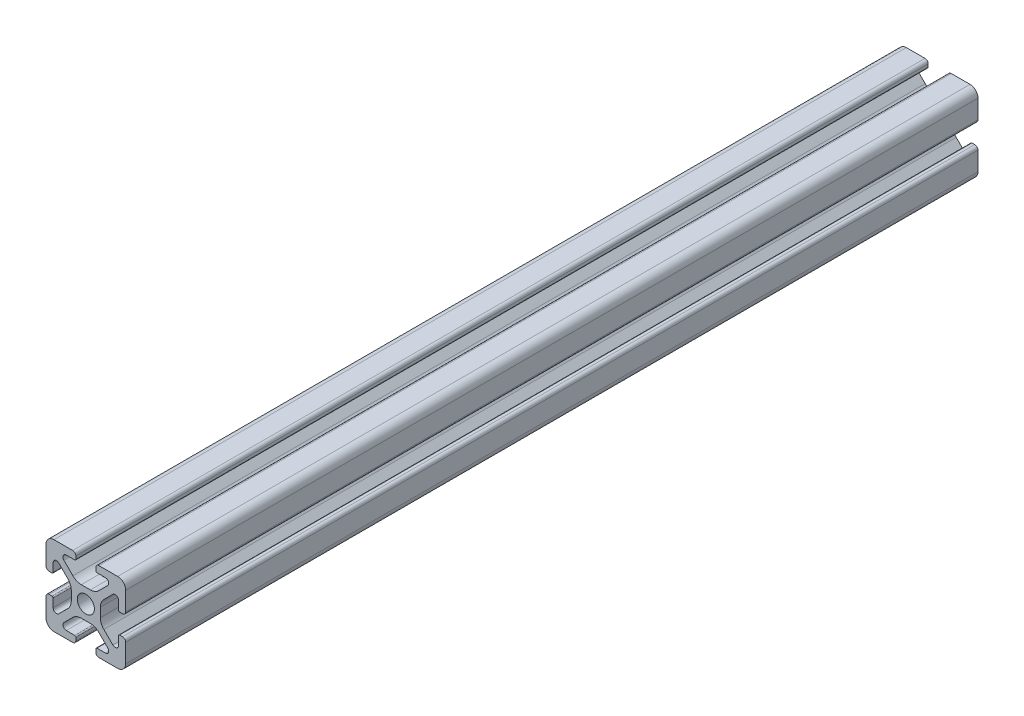
SolidWorks part; units mm, degrees
material "Alliage 1060"
ref_plane "Plan de face" through (0, 0, 0) normal (0, 0, 1) x (1, 0, 0)
ref_plane "Plan de dessus" through (0, 0, 0) normal (0, 1, 0) x (1, 0, 0)
ref_plane "Plan de droite" through (0, 0, 0) normal (1, 0, 0) x (0, 0, -1)
ref_plane "Plan1" through (0, 0, 0) normal (0, 0, -1) x (-1, 0, 0)
sketch "Esquisse1" plane through (0, 0, 0) normal (0, 0, -1) x (-1, 0, 0)
  line L0 (-18, 0) -> (-13.3, 0)
  line L1 (-12.8, 1.8) -> (-14.9184, 1.8)
  line L2 (-15.5064, 3.2196) -> (-13.2547, 5.4713)
  line L3 (-11.1334, 6.35) -> (-8.8666, 6.35)
  line L4 (-6.7453, 5.4713) -> (-4.4936, 3.2196)
  line L5 (-5.0816, 1.8) -> (-7.2, 1.8)
  line L6 (-6.7, 0) -> (-2, 0)
  line L7 (0, 2) -> (0, 6.7)
  line L8 (-1.8, 7.2) -> (-1.8, 5.0816)
  line L9 (-3.2196, 4.4936) -> (-5.4713, 6.7453)
  line L10 (-6.35, 8.8666) -> (-6.35, 11.1334)
  line L11 (-5.4713, 13.2547) -> (-3.2196, 15.5064)
  line L12 (-1.8, 14.9184) -> (-1.8, 12.8)
  line L13 (0, 13.3) -> (0, 18)
  line L14 (-2, 20) -> (-6.7, 20)
  line L15 (-7.2, 18.2) -> (-5.0816, 18.2)
  line L16 (-4.4936, 16.7804) -> (-6.7453, 14.5287)
  line L17 (-8.8666, 13.65) -> (-11.1334, 13.65)
  line L18 (-13.2547, 14.5287) -> (-15.5064, 16.7804)
  line L19 (-14.9184, 18.2) -> (-12.8, 18.2)
  line L20 (-13.3, 20) -> (-18, 20)
  line L21 (-20, 18) -> (-20, 13.3)
  line L22 (-16.7804, 15.5064) -> (-14.5287, 13.2547)
  line L23 (-13.65, 11.1334) -> (-13.65, 8.8666)
  line L24 (-14.5287, 6.7453) -> (-16.7804, 4.4936)
  line L25 (-18.2, 5.0816) -> (-18.2, 7.2)
  line L26 (-20, 6.7) -> (-20, 2)
  arc A0 (-20, 2) -> (-18, 0) centre (-18, 2) ccw
  arc A1 (-13.3, 0) -> (-12.5, 0.8) centre (-13.3, 0.8) ccw
  arc A2 (-12.5, 1.5) -> (-12.8, 1.8) centre (-12.8, 1.5) ccw
  arc A3 (-14.9184, 1.8) -> (-15.5064, 3.2196) centre (-14.9184, 2.6316) cw
  arc A4 (-13.2547, 5.4713) -> (-11.1334, 6.35) centre (-11.1334, 3.35) cw
  arc A5 (-8.8666, 6.35) -> (-6.7453, 5.4713) centre (-8.8666, 3.35) cw
  arc A6 (-4.4936, 3.2196) -> (-5.0816, 1.8) centre (-5.0816, 2.6316) cw
  arc A7 (-7.2, 1.8) -> (-7.5, 1.5) centre (-7.2, 1.5) ccw
  arc A8 (-7.5, 0.8) -> (-6.7, 0) centre (-6.7, 0.8) ccw
  arc A9 (-2, 0) -> (0, 2) centre (-2, 2) ccw
  arc A10 (0, 6.7) -> (-0.8, 7.5) centre (-0.8, 6.7) ccw
  arc A11 (-1.5, 7.5) -> (-1.8, 7.2) centre (-1.5, 7.2) ccw
  arc A12 (-1.8, 5.0816) -> (-3.2196, 4.4936) centre (-2.6316, 5.0816) cw
  arc A13 (-5.4713, 6.7453) -> (-6.35, 8.8666) centre (-3.35, 8.8666) cw
  arc A14 (-6.35, 11.1334) -> (-5.4713, 13.2547) centre (-3.35, 11.1334) cw
  arc A15 (-3.2196, 15.5064) -> (-1.8, 14.9184) centre (-2.6316, 14.9184) cw
  arc A16 (-1.8, 12.8) -> (-1.5, 12.5) centre (-1.5, 12.8) ccw
  arc A17 (-0.8, 12.5) -> (0, 13.3) centre (-0.8, 13.3) ccw
  arc A18 (0, 18) -> (-2, 20) centre (-2, 18) ccw
  arc A19 (-6.7, 20) -> (-7.5, 19.2) centre (-6.7, 19.2) ccw
  arc A20 (-7.5, 18.5) -> (-7.2, 18.2) centre (-7.2, 18.5) ccw
  arc A21 (-5.0816, 18.2) -> (-4.4936, 16.7804) centre (-5.0816, 17.3684) cw
  arc A22 (-6.7453, 14.5287) -> (-8.8666, 13.65) centre (-8.8666, 16.65) cw
  arc A23 (-11.1334, 13.65) -> (-13.2547, 14.5287) centre (-11.1334, 16.65) cw
  arc A24 (-15.5064, 16.7804) -> (-14.9184, 18.2) centre (-14.9184, 17.3684) cw
  arc A25 (-12.8, 18.2) -> (-12.5, 18.5) centre (-12.8, 18.5) ccw
  arc A26 (-12.5, 19.2) -> (-13.3, 20) centre (-13.3, 19.2) ccw
  arc A27 (-18, 20) -> (-20, 18) centre (-18, 18) ccw
  arc A28 (-20, 13.3) -> (-19.2, 12.5) centre (-19.2, 13.3) ccw
  arc A29 (-18.5, 12.5) -> (-18.2, 12.8) centre (-18.5, 12.8) ccw
  arc A30 (-18.2, 14.9184) -> (-16.7804, 15.5064) centre (-17.3684, 14.9184) cw
  arc A31 (-14.5287, 13.2547) -> (-13.65, 11.1334) centre (-16.65, 11.1334) cw
  arc A32 (-13.65, 8.8666) -> (-14.5287, 6.7453) centre (-16.65, 8.8666) cw
  arc A33 (-16.7804, 4.4936) -> (-18.2, 5.0816) centre (-17.3684, 5.0816) cw
  arc A34 (-18.2, 7.2) -> (-18.5, 7.5) centre (-18.5, 7.2) ccw
  arc A35 (-19.2, 7.5) -> (-20, 6.7) centre (-19.2, 6.7) ccw
  circle A36 centre (-10, 10) radius 2.15
  spline S0 degree 1 poles (-12.5, 1.5) (-12.5, 0.8) knots 0 0 0.7 0.7
  spline S1 degree 1 poles (-7.5, 0.8) (-7.5, 1.5) knots 0 0 0.7 0.7
  spline S2 degree 1 poles (-1.5, 7.5) (-0.8, 7.5) knots 0 0 0.7 0.7
  spline S3 degree 1 poles (-0.8, 12.5) (-1.5, 12.5) knots 0 0 0.7 0.7
  spline S4 degree 1 poles (-7.5, 18.5) (-7.5, 19.2) knots 0 0 0.7 0.7
  spline S5 degree 1 poles (-12.5, 19.2) (-12.5, 18.5) knots 0 0 0.7 0.7
  spline S6 degree 1 poles (-18.5, 12.5) (-19.2, 12.5) knots 0 0 0.7 0.7
  spline S7 degree 1 poles (-18.2, 14.9184) (-18.2, 12.8) knots 0 0 2.118424 2.118424
  spline S8 degree 1 poles (-19.2, 7.5) (-18.5, 7.5) knots 0 0 0.7 0.7
extrude "Extrusion1" add sketch "Esquisse1" against normal blind 214
hole_wizard "Trou taraudé M61" positions "Esquisse3" profile "Esquisse2" tap size "M6" standard "ISO" end condition through all
sketch "Esquisse3" plane through (0, 0, 0) normal (0, -1, 0) x (-1, 0, 0)
  point P0 (-10, -207)
sketch "Esquisse2" plane through (10, 0, 207) normal (1, 0, 0) x (0, 0, -1)
  line L0 (0, 0) -> (0, 20)
  line L1 (0, 20) -> (2.5, 20)
  line L2 (2.5, 20) -> (2.5, 0)
  line L5 (2.5, 0) -> (0, 0)
  line L11 (0, -6.35) -> (0, 107.95) construction
  dimension "Diamètre du trou pour taraudage jusqu'au prochain" = 5
  dimension "Profondeur du trou pour taraudage jusqu'au prochain" = 20
cosmetic thread "Filetage de perçage6" parameters "D2"=6
hole_wizard "Trou taraudé M51" positions "Esquisse5" profile "Esquisse4" tap size "M5" standard "ISO" end condition through all
sketch "Esquisse5" plane through (0, 0, 0) normal (0, -1, 0) x (-1, 0, 0)
  point P0 (-10, -10)
  point P3 (455.3, -207)
sketch "Esquisse4" plane through (10, 0, 10) normal (1, 0, 0) x (0, 0, -1)
  line L0 (0, 0) -> (0, 20)
  line L1 (0, 20) -> (2.1, 20)
  line L2 (2.1, 20) -> (2.1, 0)
  line L5 (2.1, 0) -> (0, 0)
  line L11 (0, -6.35) -> (0, 107.95) construction
  dimension "Diamètre du trou pour taraudage jusqu'au prochain" = 4.2
  dimension "Profondeur du trou pour taraudage jusqu'au prochain" = 20
cosmetic thread "Filetage de perçage7" parameters "D2"=5
